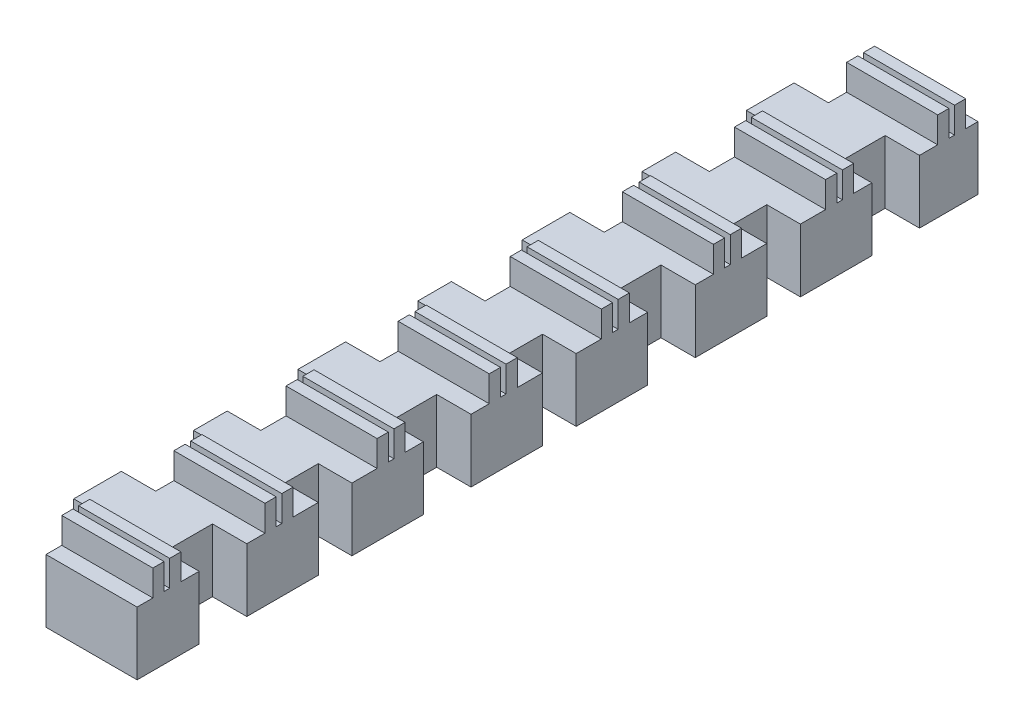
SolidWorks part; units mm, degrees
ref_plane "Front Plane" through (0, 0, 0) normal (0, 0, 1) x (1, 0, 0)
ref_plane "Top Plane" through (0, 0, 0) normal (0, 1, 0) x (1, 0, 0)
ref_plane "Right Plane" through (0, 0, 0) normal (1, 0, 0) x (0, 0, -1)
sketch "Sketch1" plane through (0, 0, 0) normal (0, 1, 0) x (1, 0, 0)
  line L1 (-6.5, -60) -> (6.5, -60)
  line L2 (-6.5, -60) -> (-6.5, 60)
  line L3 (-6.5, 60) -> (6.5, 60)
  line L4 (6.5, -60) -> (6.5, 60)
  line L5 (-6.5, -60) -> (6.5, 60) construction
  line L6 (-6.5, 60) -> (6.5, -60) construction
  point P0 (0, 0)
  dimension "D1" = 13
  dimension "D2" = 120
extrude "Boss-Extrude1" add sketch "Sketch1" along normal blind 9
sketch "Sketch2" plane through (0, 9, 0) normal (0, 1, 0) x (1, 0, 0)
  line L0 (-6.5, 60) -> (-6.5, -60) construction
  line L1 (-6.5, 51.6518) -> (-11.4, 51.6518)
  line L2 (-6.5, 51.6518) -> (-6.5, 44.8518)
  line L3 (-6.5, 44.8518) -> (-11.4, 44.8518)
  line L4 (-11.4, 51.6518) -> (-11.4, 44.8518)
  line L5 (6.5, 60) -> (-6.5, 60) construction
  dimension "D1" = 4.9
  dimension "D2" = 6.8
  dimension "D3" = 8.3482
extrude "Boss-Extrude2" add sketch "Sketch2" against normal up to surface (9 mm away) up to face at (0, 0, 0)
pattern_linear "LPattern1" count 4 spacing 32 along (0, 0, 1) of "Boss-Extrude2"
sketch "Sketch3" plane through (0, 9, 0) normal (0, 1, 0) x (1, 0, 0)
  line L0 (-6.5, 44.8518) -> (-6.5, 19.6518) construction
  line L1 (-6.5, 34.6564) -> (-11.3, 34.6564)
  line L2 (-6.5, 34.6564) -> (-6.5, 29.8564)
  line L3 (-6.5, 29.8564) -> (-11.3, 29.8564)
  line L4 (-11.3, 34.6564) -> (-11.3, 29.8564)
  line L5 (6.5, 60) -> (-6.5, 60) construction
  dimension "D1" = 4.8
  dimension "D2" = 25.3436
extrude "Boss-Extrude3" add sketch "Sketch3" against normal up to surface (9 mm away) up to face at (-7.16, 0, -0.2015)
pattern_linear "LPattern2" count 3 spacing 32 along (0, 0, 1) of "Boss-Extrude3"
sketch "Sketch4" plane through (0, 0, 51.1482) normal (0, 0, 1) x (1, 0, 0)
  line L0 (-11.4, 0) -> (-6.5, 0) construction
  line L1 (-6.5, 0) -> (-6.5, 9) construction
  circle A0 centre (-9.5, 3) radius 1.5
  dimension "D1" = 3
  dimension "D2" = 3
  dimension "D3" = 3
extrude "Cut-Extrude1" cut sketch "Sketch4" against normal blind 9.6
sketch "Sketch5" plane through (0, 0, -51.6518) normal (0, 0, -1) x (-1, 0, 0)
  line L0 (6.5, 0) -> (11.4, 0) construction
  line L1 (6.5, 0) -> (6.5, 9) construction
  circle A0 centre (9.5, 3) radius 1.5
  dimension "D1" = 3
  dimension "D2" = 3
  dimension "D3" = 3
extrude "Cut-Extrude2" cut sketch "Sketch5" against normal blind 9.6
sketch "Sketch6" plane through (0, 9, 0) normal (0, 1, 0) x (1, 0, 0)
  line L0 (6.5, -60) -> (6.5, 60) construction
  line L1 (-6.5, 58.25) -> (6.5, 58.25)
  line L2 (-6.5, 58.25) -> (-6.5, 56.65)
  line L3 (-6.5, 56.65) -> (6.5, 56.65)
  line L4 (6.5, 58.25) -> (6.5, 56.65)
  line L5 (-6.5, 60) -> (-6.5, 51.6518) construction
  line L6 (6.5, 55.85) -> (-6.5, 55.85)
  line L7 (6.5, 55.85) -> (6.5, 54.25)
  line L8 (6.5, 54.25) -> (-6.5, 54.25)
  line L9 (-6.5, 55.85) -> (-6.5, 54.25)
  line L10 (6.5, 60) -> (-6.5, 60) construction
  point P13 (0, 0)
  dimension "D1" = 1.6
  dimension "D2" = 0.8
  dimension "D3" = 1.75
extrude "Boss-Extrude4" add sketch "Sketch6" along normal blind 3.7
pattern_linear "LPattern3" count 8 spacing 16 along (0, 0, 1) of "Boss-Extrude4"
sketch "Sketch7" plane through (0, 9, 0) normal (0, 1, 0) x (1, 0, 0)
  line L0 (6.5, 42.25) -> (6.5, 54.25) construction
  line L1 (6.5, 51.6518) -> (1.6, 51.6518)
  line L2 (6.5, 51.6518) -> (6.5, 44.8518)
  line L3 (6.5, 44.8518) -> (1.6, 44.8518)
  line L4 (1.6, 51.6518) -> (1.6, 44.8518)
  line L5 (-6.5, 51.6518) -> (-11.4, 51.6518) construction
  line L6 (-11.4, 44.8518) -> (-6.5, 44.8518) construction
extrude "Cut-Extrude3" cut sketch "Sketch7" against normal up to surface (9 mm away) up to face at (-7.8125, 0, -0.2221)
sketch "Sketch8" plane through (0, 9, 0) normal (0, 1, 0) x (1, 0, 0)
  line L0 (6.5, 26.25) -> (6.5, 38.25) construction
  line L1 (6.5, 34.6564) -> (1.7, 34.6564)
  line L2 (6.5, 34.6564) -> (6.5, 29.8564)
  line L3 (6.5, 29.8564) -> (1.7, 29.8564)
  line L4 (1.7, 34.6564) -> (1.7, 29.8564)
  line L5 (-6.5, 34.6564) -> (-11.3, 34.6564) construction
  line L6 (-11.3, 29.8564) -> (-6.5, 29.8564) construction
extrude "Cut-Extrude4" cut sketch "Sketch8" against normal up to surface (9 mm away) up to face at (-6.4944, 0, -5.5587)
pattern_linear "LPattern4" count 4 spacing 32 along (0, 0, 1) of "Cut-Extrude3"
pattern_linear "LPattern5" count 3 spacing 32 along (0, 0, 1) of "Cut-Extrude4"
